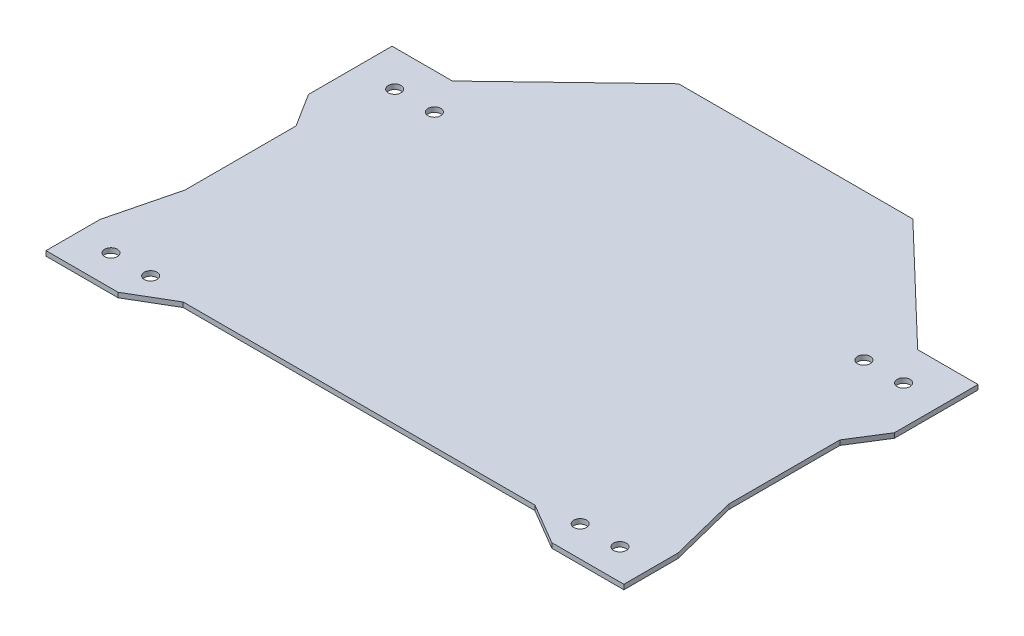
SolidWorks part; units mm, degrees
ref_plane "Front Plane" through (0, 0, 0) normal (0, 0, 1) x (1, 0, 0)
ref_plane "Top Plane" through (0, 0, 0) normal (0, 1, 0) x (1, 0, 0)
ref_plane "Right Plane" through (0, 0, 0) normal (1, 0, 0) x (0, 0, -1)
sketch "Sketch1" plane through (0, 0, 0) normal (0, 1, 0) x (1, 0, 0)
  line L0 (41.275, 184.523) -> (-41.275, 184.523)
  line L5 (-41.275, 184.523) -> (-82, 145.4942)
  line L6 (-82, 145.4942) -> (-103.2688, 145.4942)
  line L7 (-103.2688, 145.4942) -> (-103.2688, 116.0511)
  line L8 (-103.2688, 116.0511) -> (-95.8438, 104.2192)
  line L9 (-95.8438, 104.2192) -> (-95.8438, 65.099)
  line L10 (-95.8438, 65.099) -> (-101.8437, 41.1442)
  line L11 (-101.8437, 41.1442) -> (-101.8437, 22.0942)
  line L12 (-101.8437, 22.0942) -> (-76.4437, 22.0942)
  line L13 (-76.4437, 22.0942) -> (-61.9938, 30.599)
  line L14 (-61.9938, 30.599) -> (61.9938, 30.599)
  line L15 (0, 184.523) -> (0, 30.599) construction
  line L16 (76.4438, 22.0942) -> (61.9938, 30.599)
  line L17 (101.8438, 22.0942) -> (76.4438, 22.0942)
  line L18 (101.8438, 41.1442) -> (101.8438, 22.0942)
  line L19 (95.8438, 65.099) -> (101.8438, 41.1442)
  line L20 (95.8438, 104.2192) -> (95.8438, 65.099)
  line L21 (103.2688, 116.0511) -> (95.8438, 104.2192)
  line L22 (103.2688, 145.4942) -> (103.2688, 116.0511)
  line L23 (82, 145.4942) -> (103.2688, 145.4942)
  line L24 (41.275, 184.523) -> (82, 145.4942)
  line L25 (-764.9926, 2181.3441) -> (1547.3756, 2181.3441) construction
  line L26 (177.1878, 116.7003) -> (177.1878, 54.6539) construction
  line L27 (524.0183, 203.5246) -> (677.9423, 203.5246) construction
  line L28 (-101.8437, 32.849) -> (-89.6937, 32.849) construction
  line L29 (-89.6937, 32.849) -> (-89.6937, 22.0942) construction
  line L30 (-61.9938, 30.599) -> (-89.6937, 30.599) construction
  line L31 (-75.6937, 32.849) -> (-89.6937, 32.849) construction
  line L32 (-103.2688, 132.8442) -> (-89.6938, 132.8442) construction
  line L33 (-89.6938, 132.8442) -> (-89.6938, 145.4942) construction
  line L34 (-89.6938, 132.8442) -> (-75.6938, 132.8442) construction
  line L35 (-89.6938, 132.8442) -> (-89.6937, 32.849) construction
  circle A0 centre (-89.6937, 32.849) radius 2.25
  circle A1 centre (-75.6937, 32.849) radius 2.25
  circle A2 centre (-89.6938, 132.8442) radius 2.25
  circle A3 centre (-75.6938, 132.8442) radius 2.25
  circle A4 centre (75.6938, 32.849) radius 2.25
  circle A5 centre (89.6938, 32.849) radius 2.25
  circle A6 centre (75.6938, 132.8442) radius 2.25
  circle A7 centre (89.6938, 132.8442) radius 2.25
  dimension "D10" = 4.5
  dimension "D4" = 179.3875
  dimension "D1" = 153.924
  dimension "D2" = 153.924
  dimension "D3" = 123.4
  dimension "D5" = 82.55
  dimension "D6" = 164
  dimension "D8" = 25.4
  dimension "D9" = 19.05
  dimension "D11" = 12.15
  dimension "D12" = 10.7548
  dimension "D13" = 32.25
  dimension "D14" = 41.275
  dimension "D16" = 12.65
  dimension "D17" = 14
extrude "Boss-Extrude1" add sketch "Sketch1" along normal blind 1.7
